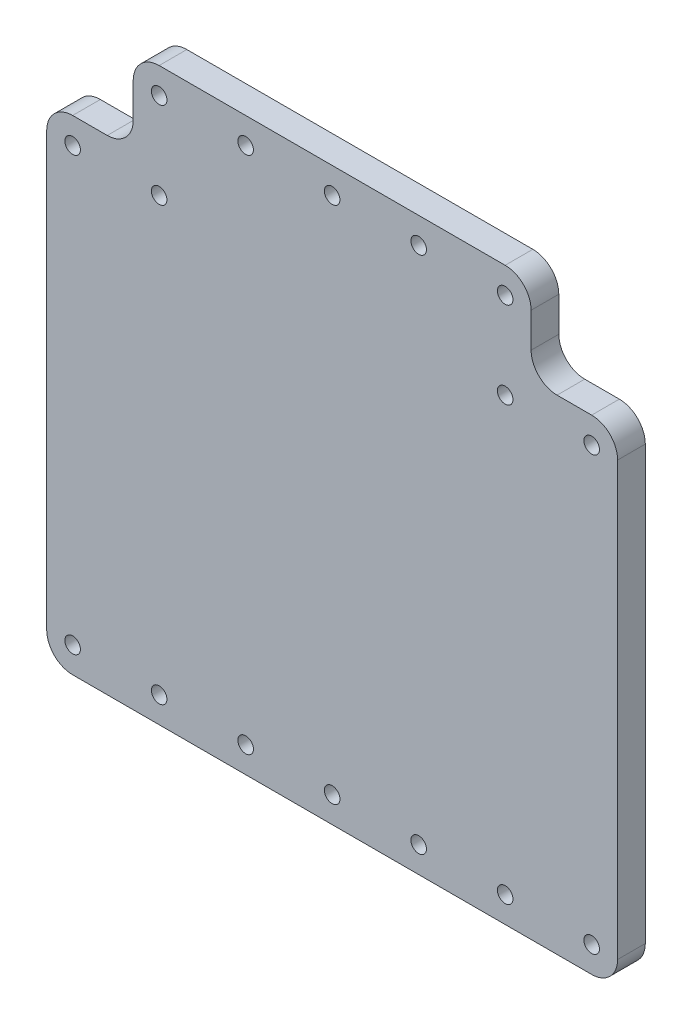
SolidWorks part; units mm, degrees
ref_plane "Front Plane" through (0, 0, 0) normal (0, 0, 1) x (1, 0, 0)
ref_plane "Top Plane" through (0, 0, 0) normal (0, 1, 0) x (1, 0, 0)
ref_plane "Right Plane" through (0, 0, 0) normal (1, 0, 0) x (0, 0, -1)
sketch "Sketch2" plane through (0, 0, 0) normal (0, 0, 1) x (1, 0, 0)
  line L5 (-57.5, 60) -> (-57.5, 50)
  line L6 (-75, -97.5) -> (75, -97.5)
  line L24 (-82.5, -90) -> (-82.5, 35)
  line L25 (-50, 67.5) -> (50, 67.5)
  line L26 (82.5, -90) -> (82.5, 35)
  line L27 (0, -100) -> (0, 100) construction
  line L28 (-100, 0) -> (100, 0) construction
  line L29 (-65, 42.5) -> (-75, 42.5)
  line L34 (57.5, 60) -> (57.5, 50)
  line L35 (65, 42.5) -> (75, 42.5)
  arc A12 (-82.5, 35) -> (-75, 42.5) centre (-75, 35) cw
  arc A19 (82.5, 35) -> (75, 42.5) centre (75, 35) ccw
  arc A20 (65, 42.5) -> (57.5, 50) centre (65, 50) cw
  arc A21 (57.5, 60) -> (50, 67.5) centre (50, 60) ccw
  arc A22 (-50, 67.5) -> (-57.5, 60) centre (-50, 60) ccw
  arc A23 (-65, 42.5) -> (-57.5, 50) centre (-65, 50) ccw
  arc A24 (-82.5, -90) -> (-75, -97.5) centre (-75, -90) ccw
  arc A25 (82.5, -90) -> (75, -97.5) centre (75, -90) cw
  point P0 (0, 0)
  point P39 (-57.5, 67.5)
  dimension "D5" = 25
  dimension "D6" = 82.5
  dimension "D7" = 7.5
  dimension "D2" = 25
  dimension "D3" = 165
  dimension "D8" = 7.5
  dimension "D1" = 67.5
  dimension "D4" = 82.5
extrude "Boss-Extrude1" add sketch "Sketch2" against normal blind 8
sketch "Sketch3" plane through (0, 0, -8) normal (0, 0, -1) x (-1, 0, 0)
  point P0 (-75, 35)
  point P3 (-50, 35)
  point P6 (-50, 60)
  point P9 (-25, 60)
  point P12 (0, 60)
  point P15 (25, 60)
  point P18 (50, 60)
  point P21 (50, 35)
  point P24 (75, 35)
  point P27 (-75, -90)
  point P30 (-50, -90)
  point P33 (-25, -90)
  point P36 (0, -90)
  point P39 (25, -90)
  point P42 (50, -90)
  point P45 (75, -90)
hole_wizard "CBORE for M4 SHCS1" positions "Sketch3" profile "Sketch4" counterbore size "M4" standard "ANSI Metric" end condition through all
sketch "Sketch4" plane through (75, 35, -8) normal (1, 0, 0) x (0, 1, 0)
  line L0 (0, 0) -> (0, 8)
  line L1 (0, 8) -> (2.25, 8)
  line L3 (2.25, 8) -> (2.25, 4)
  line L4 (2.25, 4) -> (4, 4)
  line L5 (4, 4) -> (4, 0)
  line L7 (4, 0) -> (0, 0)
  line L11 (0, -6.35) -> (0, 107.95) construction
  dimension "Thru Hole Dia." = 4.5
  dimension "Thru Hole Depth" = 8
  dimension "C'Bore Dia." = 8
  dimension "C'Bore Depth" = 4
